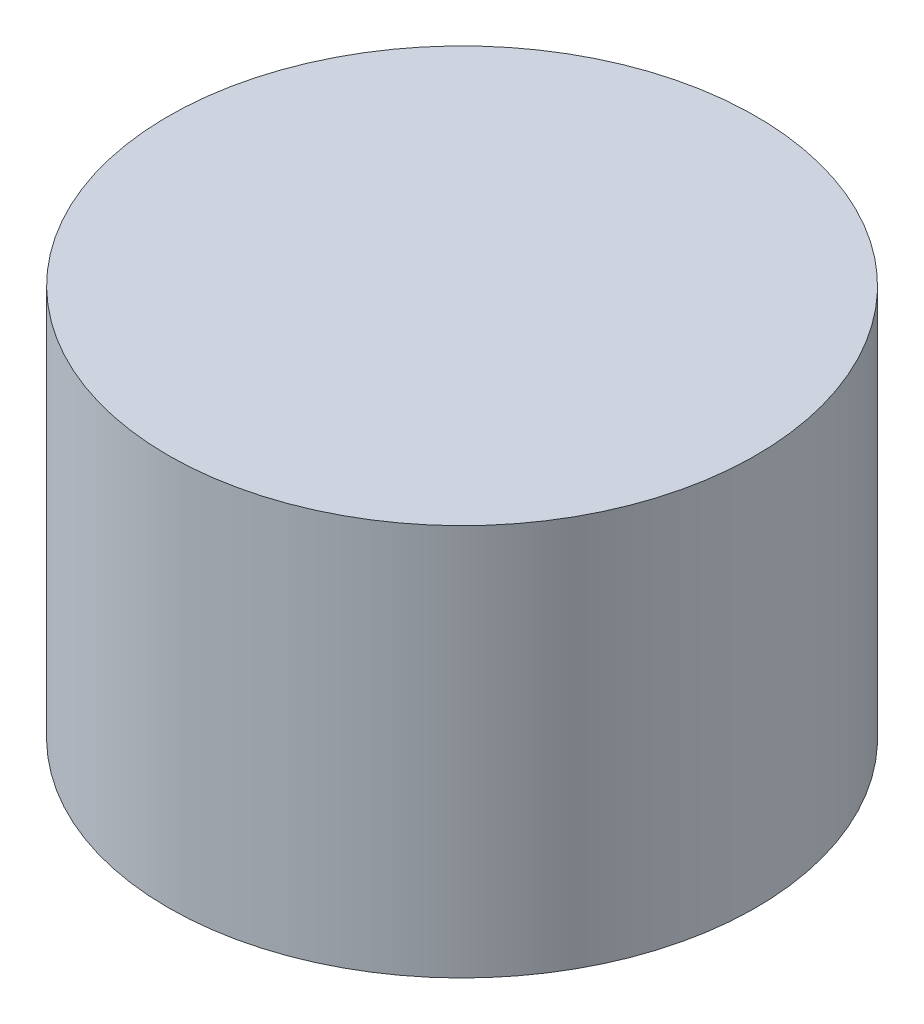
SolidWorks part; units mm, degrees
ref_plane "前基準面" through (0, 0, 0) normal (0, 0, 1) x (1, 0, 0)
ref_plane "上基準面" through (0, 0, 0) normal (0, 1, 0) x (1, 0, 0)
ref_plane "右基準面" through (0, 0, 0) normal (1, 0, 0) x (0, 0, -1)
sketch "草圖1" plane through (0, 0, 0) normal (0, 1, 0) x (1, 0, 0)
  circle A0 centre (0, 0) radius 3
  dimension "D1" = 6
extrude "填料-伸長1" add sketch "草圖1" along normal blind 4
